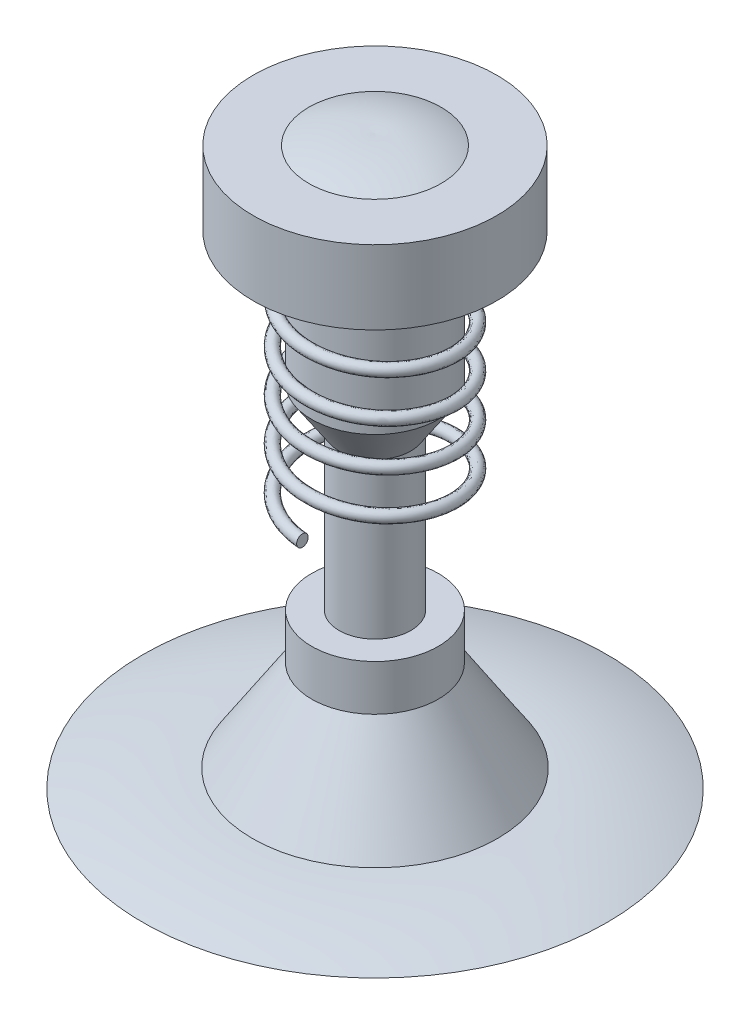
SolidWorks part; units mm, degrees
ref_plane "Front Plane" through (0, 0, 0) normal (0, 0, 1) x (1, 0, 0)
ref_plane "Top Plane" through (0, 0, 0) normal (0, 1, 0) x (1, 0, 0)
ref_plane "Right Plane" through (0, 0, 0) normal (1, 0, 0) x (0, 0, -1)
sketch "Sketch1" plane through (0, 0, 0) normal (0, 0, 1) x (1, 0, 0)
  line L0 (-0.0076, 1.699) -> (-0.0076, -0.991)
  line L1 (-0.0076, -0.991) -> (1.0924, -0.991)
  line L2 (0.5733, -0.9058) -> (0.2924, -0.4744)
  line L3 (0.2924, -0.4744) -> (0.2924, -0.2577)
  line L4 (0.2924, -0.2577) -> (0.1624, -0.2577)
  line L5 (0.1624, -0.2577) -> (0.1624, 0.4793)
  line L6 (0.1624, 0.4793) -> (0.2924, 0.674)
  line L7 (0.2924, 0.674) -> (0.2924, 1.299)
  line L8 (0.2924, 1.299) -> (0.5696, 1.299)
  line L9 (0.5696, 1.299) -> (0.5696, 1.649)
  line L10 (0.5696, 1.649) -> (0.3059, 1.649)
  arc A0 (1.0924, -0.991) -> (0.5733, -0.9058) centre (0.5696, -2.5527) ccw
  arc A2 (-0.0076, 1.699) -> (0.3059, 1.649) centre (0.0402, 0.9908) cw
  dimension "D3" = 0.35
  dimension "D1" = 2.69
  dimension "D2" = 1.1
  dimension "D4" = 0.625
  dimension "D5" = 0.17
  dimension "D6" = 0.3
  dimension "D7" = 0.3
  dimension "D8" = 0.05
revolve "Revolve1" add sketch "Sketch1" angle 360 about L0
sketch "Sketch2" plane through (0, 1.299, 0) normal (0, -1, 0) x (1, 0, 0)
  circle A0 centre (-0.0076, 0) radius 0.344
  dimension "D1" = 0.688
curve "Helix/Spiral1" pitch 0.2 height 1.1 turns 5.5
sketch "Sketch3" plane through (0, 0, 0) normal (0, 0, 1) x (1, 0, 0)
  circle A0 centre (0.3364, 0.749) radius 0.0275
  point P4 (0, 0)
  dimension "D1" = 0.055
sweep "Sweep1" add profiles "Sketch3" path "Helix/Spiral1"
